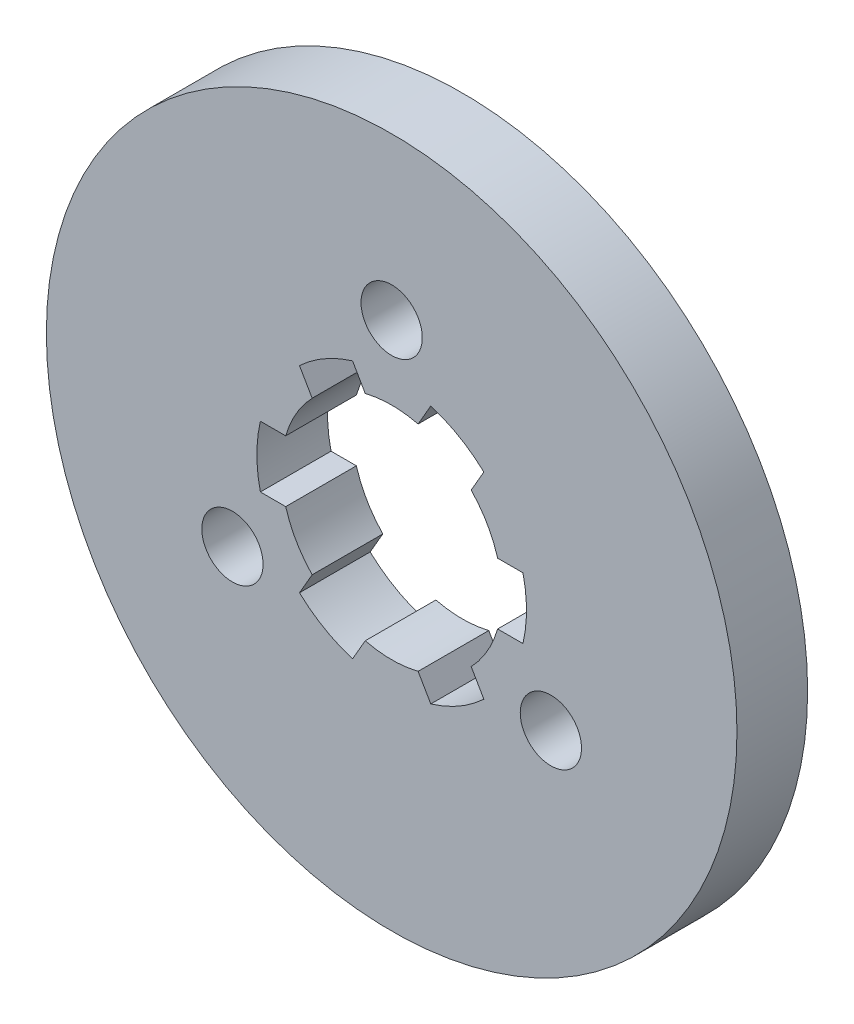
SolidWorks part; units mm, degrees
ref_plane "Front Plane" through (0, 0, 0) normal (0, 0, 1) x (1, 0, 0)
ref_plane "Top Plane" through (0, 0, 0) normal (0, 1, 0) x (1, 0, 0)
ref_plane "Right Plane" through (0, 0, 0) normal (1, 0, 0) x (0, 0, -1)
sketch "Sketch1" plane through (0, 0, 0) normal (0, 0, 1) x (1, 0, 0)
  line L0 (-10.7121, 2.5) -> (-8.6458, 2.5)
  line L1 (-10.7121, -2.5) -> (-8.6458, -2.5)
  line L2 (-9.679, 2.5) -> (-9.679, -2.5) construction
  line L3 (-3.191, 10.527) -> (-2.1578, 8.7375)
  line L4 (-7.5211, 8.027) -> (-6.488, 6.2375)
  line L5 (7.5211, 8.027) -> (6.488, 6.2375)
  line L6 (3.191, 10.527) -> (2.1578, 8.7375)
  line L7 (10.7121, -2.5) -> (8.6458, -2.5)
  line L8 (10.7121, 2.5) -> (8.6458, 2.5)
  line L9 (3.191, -10.527) -> (2.1578, -8.7375)
  line L10 (7.5211, -8.027) -> (6.488, -6.2375)
  line L11 (-7.5211, -8.027) -> (-6.488, -6.2375)
  line L12 (-3.191, -10.527) -> (-2.1578, -8.7375)
  circle A0 centre (0, 0) radius 28.1739
  arc A1 (-8.6458, -2.5) -> (-6.488, -6.2375) centre (0, 0) ccw
  arc A2 (-10.7121, 2.5) -> (-10.7121, -2.5) centre (0, 0) ccw
  arc A3 (-6.488, 6.2375) -> (-8.6458, 2.5) centre (0, 0) ccw
  arc A4 (2.1578, 8.7375) -> (-2.1578, 8.7375) centre (0, 0) ccw
  arc A5 (8.6458, 2.5) -> (6.488, 6.2375) centre (0, 0) ccw
  arc A6 (6.488, -6.2375) -> (8.6458, -2.5) centre (0, 0) ccw
  arc A7 (-2.1578, -8.7375) -> (2.1578, -8.7375) centre (0, 0) ccw
  arc A8 (-7.5211, -8.027) -> (-3.191, -10.527) centre (0, 0) ccw
  arc A9 (3.191, -10.527) -> (7.5211, -8.027) centre (0, 0) ccw
  arc A10 (10.7121, -2.5) -> (10.7121, 2.5) centre (0, 0) ccw
  arc A11 (7.5211, 8.027) -> (3.191, 10.527) centre (0, 0) ccw
  arc A12 (-3.191, 10.527) -> (-7.5211, 8.027) centre (0, 0) ccw
  circle A13 centre (0, 15) radius 2.5
  circle A14 centre (12.9904, -7.5) radius 2.5
  circle A15 centre (-12.9904, -7.5) radius 2.5
  point P11 (-9.679, 0)
  point P14 (24.6601, -11.3393)
  point P34 (0, 0)
  point P35 (0, 0)
  point P39 (0, 0)
  dimension "D1" = 56.3478
  dimension "D2" = 22
  dimension "D3" = 18
  dimension "D7" = 5
  dimension "D4" = 5
  dimension "D5" = 6
  dimension "D6" = 15
  dimension "D8" = 3
extrude "Boss-Extrude1" add sketch "Sketch1" along normal blind 5.7658
ref_plane "Motor Sprocket Middle Plane" through (0, 0, 2.8829) normal (0, 0, 1) x (1, 0, 0)
